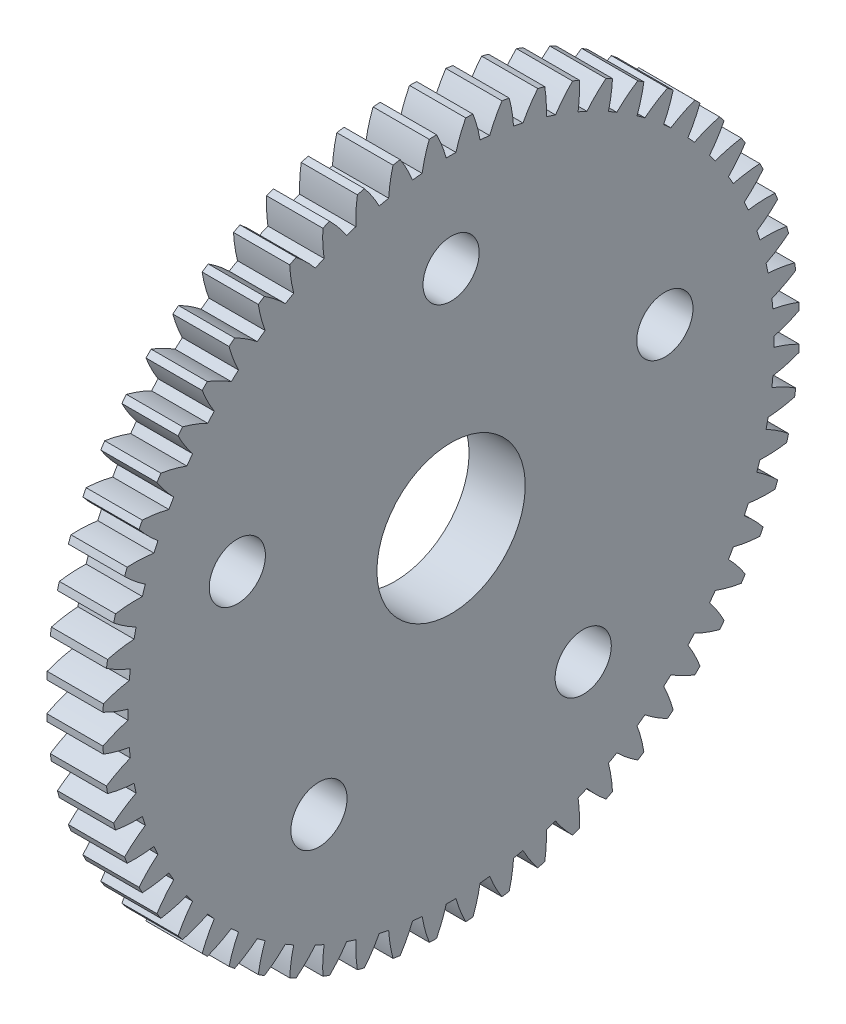
SolidWorks part; units mm, degrees
ref_plane "Plane1" through (0, 0, 0) normal (0, 0, 1) x (1, 0, 0)
ref_plane "Plane2" through (0, 0, 0) normal (0, 1, 0) x (1, 0, 0)
ref_plane "Plane3" through (0, 0, 0) normal (1, 0, 0) x (0, 0, -1)
sketch "HoldingSke" plane through (0, 0, 0) normal (0, 1, 0) x (1, 0, 0)
  line L0 (0, 0) -> (0.5, -0.866)
  line L1 (-15, 0) -> (100, 0) construction
  line L2 (0, 0) -> (-2.1039, 2.3779)
  line L3 (0, 0) -> (-11.863, 4.5341)
  line L4 (0, 0) -> (4.318, 7.479)
  line L5 (0, 0) -> (-46.8476, -17.4728)
  line L6 (0, 0) -> (-4.1448, -2.7965)
  line L7 (-2.1039, 2.3779) -> (8.6586, 51.2059)
  line L8 (-76.2, 54.61) -> (-75.7, 54.61)
  line L9 (-71.009, 38.7566) -> (-53.1078, 45.2721)
  line L10 (-76.2, 71.12) -> (104.1128, 71.12)
  line L11 (0, 0) -> (-5, 0)
  line L12 (-76.2, 101.6) -> (-76.162, 101.6)
  line L13 (24.9733, 27.94) -> (52.9518, 28.4284)
  line L14 (24.9733, 27.94) -> (24.9743, 27.94)
  line L15 (24.9733, 27.94) -> (100.4006, 29.5858)
  line L16 (-63.627, -1) -> (-12.827, -1)
  circle A0 centre (0, 0) radius 1.5
  circle A1 centre (0, 0) radius 28.749
  circle A2 centre (0, 0) radius 37.5
  circle A3 centre (0, 0) radius 1.5
  dimension "MHD" = 57.498
  dimension "Hub_dia" = 75
  dimension "Bore" = 3
  dimension "MBD" = 3
  dimension "Num_teeth" = 60
  dimension "Pitch" = 1
  dimension "Overall_len" = 50
  dimension "Show_teeth" = 60
  dimension "Thickness" = 5
  dimension "OAL" = 50.0001
  dimension "T_dim" = 0.5
  dimension "Ap" = 20
  dimension "H" = 19.05
  dimension "Pitch_radius" = 180.3128
  dimension "Width" = 5
  dimension "Backlash" = 0.038
  dimension "Addendum_fac" = 1
  dimension "Dedendum_fac" = 1.25
  dimension "Clearance_fac" = 0.25
  dimension "Dedendum_add" = 0.001
  dimension "Module" = 1
sketch "BasProSke" plane through (0, 0, 0) normal (0, 1, 0) x (1, 0, 0)
  line L0 (-10, 0) -> (60, 0) construction
  line L1 (0, 0) -> (0, 31)
  line L2 (0, 0) -> (5, 0)
  line L3 (5, 0) -> (5, 31)
  line L4 (5, 31) -> (0, 31)
  dimension "Thickness" = 5
  dimension "Diameter" = 62
revolve "Base-Revolve" add sketch "BasProSke" angle 360 about L0
sketch "TooCutSke" plane through (0, 0, 0) normal (1, 0, 0) x (0, 0, -1)
  line L1 (0, 0) -> (0, 107) construction
  line L2 (0, 0) -> (-0.8518, 29.9879) construction
  line L3 (0, 0) -> (-3.1393, 59.9006) construction
  line L4 (-0.8518, 29.9879) -> (-1.5696, 29.9503) construction
  arc A0 (0.4302, 28.7458) -> (-0.4302, 28.7458) centre (0, 0) ccw
  arc A1 (1.3127, 30.9976) -> (-1.3127, 30.9976) centre (0, 0) ccw
  circle A2 centre (0, 0) radius 30 construction
  circle A3 centre (0, 0) radius 28.1908 construction
  arc A4 (-0.4302, 28.7458) -> (-1.3127, 30.9976) centre (-11.9871, 25.5153) ccw
  arc A5 (1.3127, 30.9976) -> (0.4302, 28.7458) centre (11.9871, 25.5153) ccw
  dimension "Root_dia" = 57.498
  dimension "Overcut_dia" = 62.0508
  dimension "Pitch_dia" = 60
  dimension "Base_dia" = 56.3816
  dimension "Flank_rad" = 12
  dimension "Half_ang" = 3
  dimension "Half_CT" = 0.7188
extrude "ToothCut" cut sketch "TooCutSke" along normal through all
fillet "Breaks" [suppressed] radius 0.02
fillet "RootFillets" [suppressed] radius 0.251
pattern_circular "TeethCuts" count 60 over 360 about axis through (0, 0, 0) along (1, 0, 0) of "ToothCut", "RootFillets", "Breaks"
sketch "HubNeaOneSke" plane through (0, 0, 0) normal (-1, 0, 0) x (0, 0, 1)
  circle A0 centre (0, 0) radius 28.749
  dimension "Diameter" = 57.498
extrude "HubNearOne" [suppressed] add sketch "HubNeaOneSke" along normal blind 45.0001
sketch "HubNeaBotSke" plane through (0, 0, 0) normal (-1, 0, 0) x (0, 0, 1)
  circle A0 centre (0, 0) radius 28.749
  dimension "Diameter" = 57.498
extrude "HubNearBoth" [suppressed] add sketch "HubNeaBotSke" along normal blind 22.5
ref_plane "FarPln" through (5, 0, 0) normal (1, 0, 0) x (0, 0, -1)
sketch "HubFarSke" plane through (5, 0, 0) normal (1, 0, 0) x (0, 0, -1)
  circle A0 centre (0, 0) radius 28.749
  dimension "Diameter" = 57.498
extrude "HubFar" [suppressed] add sketch "HubFarSke" along normal blind 22.5
sketch "BorSke" plane through (0, 0, 0) normal (1, 0, 0) x (0, 0, -1)
  circle A0 centre (0, 0) radius 6.6
  dimension "Diameter" = 13.2
extrude "Bore" cut sketch "BorSke" along normal mid plane 100.0001
sketch "KeySke" plane through (0, 0, 0) normal (1, 0, 0) x (0, 0, -1)
  line L0 (-0.6, 0) -> (-0.6, 2)
  line L1 (-0.6, 2) -> (0.6, 2)
  line L2 (0.6, 2) -> (0.6, 0)
  line L3 (0, 0) -> (0, 34) construction
  line L4 (-0.6, 0) -> (0.6, 0)
  dimension "Offset" = 2
  dimension "Width" = 1.2
extrude "Keyway" [suppressed] cut sketch "KeySke" along normal mid plane 100.0001
sketch "草图1" plane through (5, 0, 0) normal (1, 0, 0) x (0, 0, -1)
  circle A0 centre (0, 20) radius 2.5
  circle A1 centre (0, 0) radius 6.6 construction
  circle A2 centre (19.0211, 6.1803) radius 2.5
  circle A3 centre (11.7557, -16.1803) radius 2.5
  circle A4 centre (-11.7557, -16.1803) radius 2.5
  circle A5 centre (-19.0211, 6.1803) radius 2.5
  point P14 (0, 0)
  dimension "D1" = 5
  dimension "D2" = 20
  dimension "D3" = 5
extrude "切除-拉伸2" cut sketch "草图1" against normal blind 5
equation "' \"Module@HoldingSke\" = 6.35"
equation "' \"Num_teeth@HoldingSke\" = 12"
equation "' \"Ap@HoldingSke\" =  20"
equation "' \"Ap@HoldingSke\" = 20"
equation "' \"Width@HoldingSke\" = 0.5 * 25.4"
equation "' \"Hub_dia@HoldingSke\"= 1 * 25.4"
equation "' \"Hub_dia@HoldingSke\" = 1 * 25.4"
equation "' \"Overall_len@HoldingSke\" = 1.0 * 25.4"
equation "' \"Bore@HoldingSke\" = 0.75 * 25.4"
equation "' \"T_dim@HoldingSke\" = 0.1 * 25.4"
equation "' \"Width@KeySke\" = 0.25 * 25.4"
equation "' \"Show_teeth@HoldingSke\" = 13"
equation "' \"Backlash@HoldingSke\" = 0.009 * 25.4"
equation "' \"Addendum_fac@HoldingSke\" = 1.0"
equation "' \"Dedendum_fac@HoldingSke\" = 1.25"
equation "' \"Dedendum_add@HoldingSke\" = 0.00005 * 25.4"
equation "' \"Clearance_fac@HoldingSke\" = 0.25"
equation "\"Pitch@HoldingSke\" = 1 / \"Module@HoldingSke\""
equation "\"Overcut_dia@TooCutSke\" = (\"Num_teeth@HoldingSke\" + 2 * \"Addendum_fac@HoldingSke\") / \"Pitch@HoldingSke\" + 0.002 * 25.4"
equation "\"Pitch_dia@TooCutSke\" = \"Num_teeth@HoldingSke\" / \"Pitch@HoldingSke\""
equation "\"Base_dia@TooCutSke\" = \"Num_teeth@HoldingSke\" / \"Pitch@HoldingSke\" * cos((\"Ap@HoldingSke\"  * 3.14159265 / 180))"
equation "\"Root_dia@TooCutSke\" = (\"Num_teeth@HoldingSke\" + 2) / \"Pitch@HoldingSke\" - 2 * (\"Addendum_fac@HoldingSke\" + \"Dedendum_fac@HoldingSke\") / \"Pitch@HoldingSke\" - \"Dedendum_add@HoldingSke\" * 2"
equation "\"Half_ang@TooCutSke\" = 180 / \"Num_teeth@HoldingSke\""
equation "\"Half_CT@TooCutSke\" = \"Num_teeth@HoldingSke\" / \"Pitch@HoldingSke\" * sin((3.14159265 / 2 / \"Num_teeth@HoldingSke\")) / 2 - 7 * \"Backlash@HoldingSke\" / 4"
equation "\"Flank_rad@TooCutSke\" = \"Num_teeth@HoldingSke\" / \"Pitch@HoldingSke\" / 5"
equation "\"Radius@RootFillets\" = \"Clearance_fac@HoldingSke\" / \"Pitch@HoldingSke\" + \"Dedendum_add@HoldingSke\""
equation "\"Break_rad@Breaks\" = 0.02 / \"Pitch@HoldingSke\""
equation "\"Thickness@HoldingSke\" = \"Width@HoldingSke\""
equation "\"OAL@HoldingSke\" = \"Thickness@HoldingSke\""
equation "\"MHD@HoldingSke\" = (\"Num_teeth@HoldingSke\" + 2) / \"Pitch@HoldingSke\" - 2 * (\"Addendum_fac@HoldingSke\" + \"Dedendum_fac@HoldingSke\")  / \"Pitch@HoldingSke\" - \"Dedendum_add@HoldingSke\" * 2"
equation "\"MBD@HoldingSke\" = (\"Num_teeth@HoldingSke\" + 2) / \"Pitch@HoldingSke\" - 2 * (\"Addendum_fac@HoldingSke\" + \"Dedendum_fac@HoldingSke\")  / \"Pitch@HoldingSke\" - \"Dedendum_add@HoldingSke\" * 2 - 0.002 * 25.4"
equation "\"MHD@HoldingSke\" = ((sgn( \"MHD@HoldingSke\" - \"Hub_dia@HoldingSke\" )-1)*( \"MHD@HoldingSke\" - \"Hub_dia@HoldingSke\" ))/-2+ \"Hub_dia@HoldingSke\""
equation "\"MBD@HoldingSke\" = ((sgn( \"MBD@HoldingSke\" - \"Bore@HoldingSke\" )-1)*( \"MBD@HoldingSke\" - \"Bore@HoldingSke\" ))/-2+ \"Bore@HoldingSke\""
equation "\"OAL@HoldingSke\" = ((sgn( \"OAL@HoldingSke\" - \"Overall_len@HoldingSke\" )+1)*( \"OAL@HoldingSke\" - \"Overall_len@HoldingSke\" ))/2 + \"Overall_len@HoldingSke\" + 0.000002 * 25.4"
equation "\"Num_teeth@TeethCuts\" = int( \"Show_teeth@HoldingSke\" ) + 1"
equation "\"Num_teeth@TeethCuts\" = ((sgn( \"Num_teeth@TeethCuts\" - \"Num_teeth@HoldingSke\" )-1)*( \"Num_teeth@TeethCuts\" - \"Num_teeth@HoldingSke\" ))/-2+ \"Num_teeth@HoldingSke\""
equation "\"Num_teeth@TeethCuts\" = ((sgn( \"Num_teeth@TeethCuts\" - 2.0)+1)*( \"Num_teeth@TeethCuts\" - 2.0))/2 +2.0"
equation "\"Angle@TeethCuts\" = 360.0 / \"Num_teeth@HoldingSke\""
equation "\"Diameter@BasProSke\" = (\"Num_teeth@HoldingSke\" + 2 * \"Addendum_fac@HoldingSke\") / \"Pitch@HoldingSke\""
equation "\"Thickness@BasProSke\"  = \"Thickness@HoldingSke\""
equation "' \"Fillet_rad@BasProSke\" =  \"Thickness@HoldingSke\" * 0.05"
equation "' \"Fillet_rad@BasProSke\" = \"Thickness@HoldingSke\" * 0.05"
equation "\"MHD@HoldingSke\" = ((sgn( \"MHD@HoldingSke\" - \"Root_dia@TooCutSke\" )-1)*( \"MHD@HoldingSke\" - \"Root_dia@TooCutSke\" ))/-2+ \"Root_dia@TooCutSke\""
equation "\"Diameter@HubNeaOneSke\" = \"MHD@HoldingSke\""
equation "\"Length@HubNearOne\" = \"OAL@HoldingSke\" - \"Thickness@BasProSke\""
equation "\"Diameter@HubNeaBotSke\" = \"MHD@HoldingSke\""
equation "\"Length@HubNearBoth\" = ( \"OAL@HoldingSke\" - \"Thickness@BasProSke\" ) / 2.0"
equation "\"Thickness@FarPln\" = \"Thickness@BasProSke\""
equation "\"Diameter@HubFarSke\" = \"MHD@HoldingSke\""
equation "\"Length@HubFar\" = ( \"OAL@HoldingSke\" - \"Thickness@BasProSke\" ) / 2.0"
equation "\"D1@Bore\" = \"OAL@HoldingSke\" * 2.0"
equation "\"D1@Keyway\" = \"OAL@HoldingSke\" * 2.0"
equation "\"Offset@KeySke\" = \"T_dim@HoldingSke\" + \"MBD@HoldingSke\" / 2.0"
